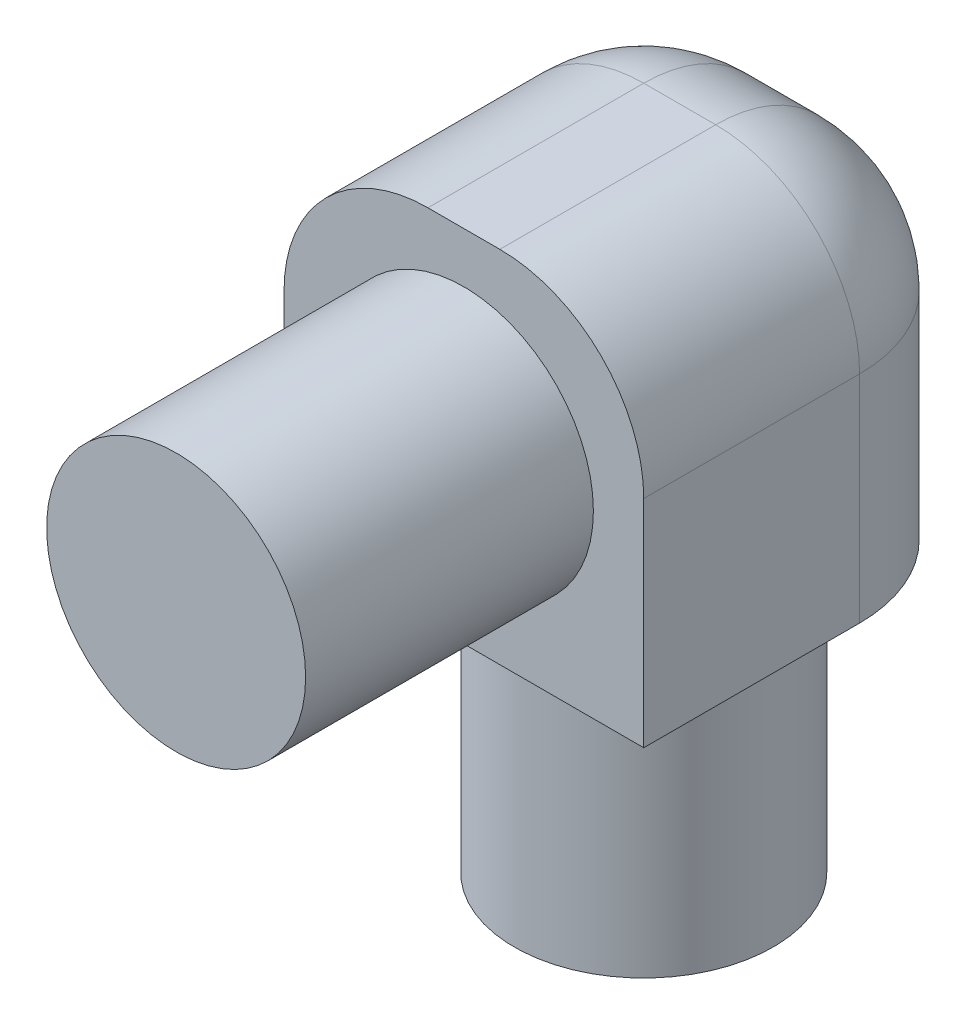
SolidWorks part; units mm, degrees
ref_plane "Front Plane" through (0, 0, 0) normal (0, 0, 1) x (1, 0, 0)
ref_plane "Top Plane" through (0, 0, 0) normal (0, 1, 0) x (1, 0, 0)
ref_plane "Right Plane" through (0, 0, 0) normal (1, 0, 0) x (0, 0, -1)
sketch "Sketch1" plane through (0, 0, 0) normal (0, 1, 0) x (1, 0, 0)
  line L0 (-25, 0) -> (25, 0) construction
  line L1 (-25, 25) -> (25, 25)
  line L2 (-25, 25) -> (-25, -25)
  line L3 (-25, -25) -> (25, -25)
  line L4 (25, 25) -> (25, -25)
  point P7 (0, 0)
  dimension "D1" = 50
  dimension "D2" = 50
extrude "Boss-Extrude1" add sketch "Sketch1" along normal blind 50
sketch "Sketch3" plane through (0, 0, 25) normal (0, 0, 1) x (1, 0, 0)
  line L0 (0, 50) -> (0, 0) construction
  line L1 (-25, 50) -> (25, 50) construction
  line L2 (-25, 25) -> (25, 25) construction
  line L3 (-25, 50) -> (-25, 0) construction
  line L4 (25, 50) -> (25, 0) construction
  circle A0 centre (0, 25) radius 18
  dimension "D1" = 36
extrude "Boss-Extrude2" add sketch "Sketch3" along normal blind 40
sketch "Sketch4" plane through (0, 0, 0) normal (0, -1, 0) x (1, 0, 0)
  line L0 (-25, 0) -> (25, 0) construction
  line L1 (-25, -25) -> (-25, 25) construction
  line L2 (25, 25) -> (25, -25) construction
  circle A0 centre (0, 0) radius 18
  dimension "D1" = 36
extrude "Boss-Extrude3" add sketch "Sketch4" along normal blind 40
fillet "Fillet1" radius 20 5 edges at (0, 50, -25) (25, 25, -25) (25, 50, 0) (-25, 25, -25) (-25, 50, 0)
